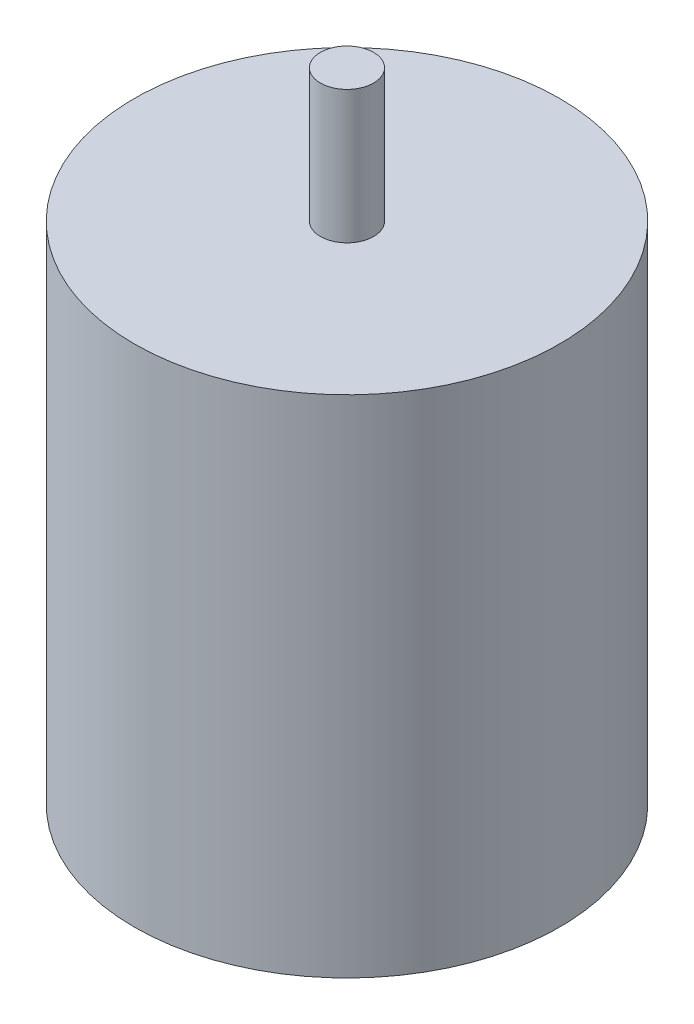
SolidWorks part; units mm, degrees
ref_plane "Front Plane" through (0, 0, 0) normal (0, 0, 1) x (1, 0, 0)
ref_plane "Top Plane" through (0, 0, 0) normal (0, 1, 0) x (1, 0, 0)
ref_plane "Right Plane" through (0, 0, 0) normal (1, 0, 0) x (0, 0, -1)
sketch "Sketch1" plane through (0, 0, 0) normal (0, 1, 0) x (1, 0, 0)
  circle A0 centre (0, 0) radius 8
  dimension "D1" = 16
extrude "Boss-Extrude1" add sketch "Sketch1" along normal blind 19
sketch "Sketch2" plane through (0, 19, 0) normal (0, 1, 0) x (1, 0, 0)
  circle A0 centre (0, 0) radius 1
  dimension "D1" = 2
extrude "Boss-Extrude2" add sketch "Sketch2" along normal blind 5
